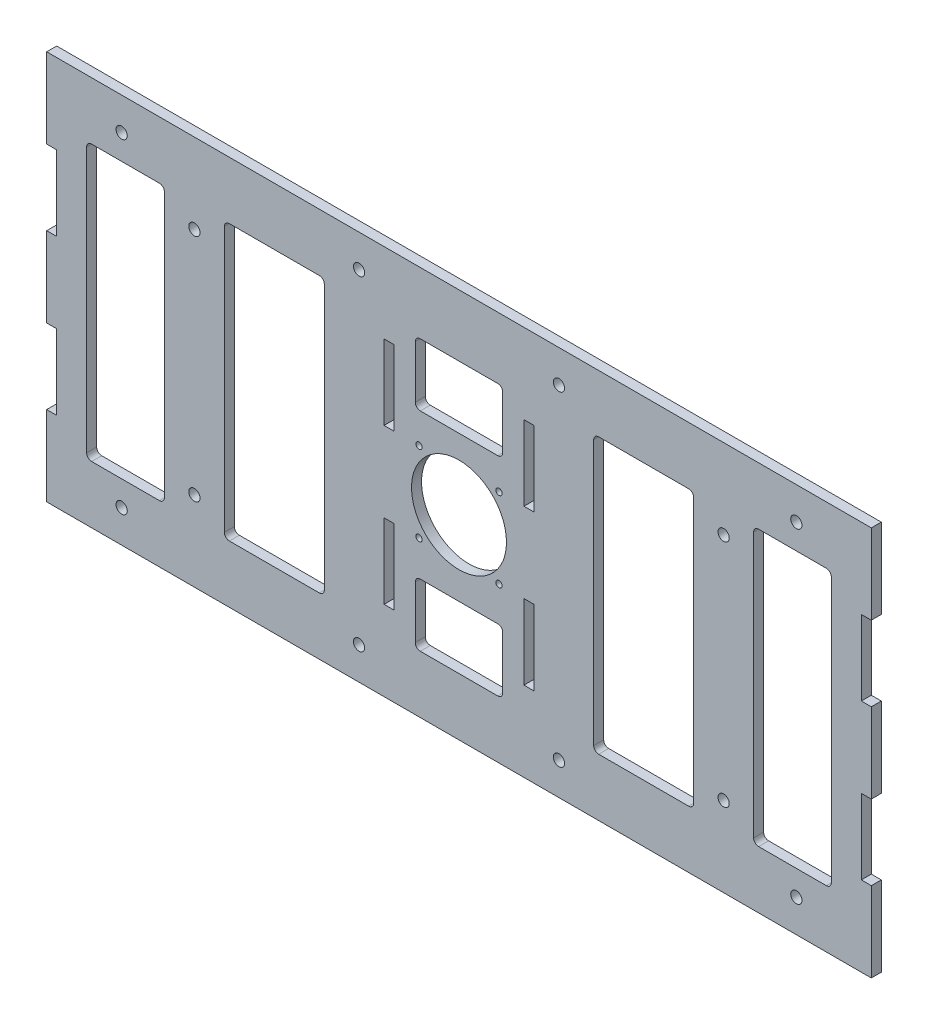
SolidWorks part; units mm, degrees
ref_plane "Ebene vorne" through (0, 0, 0) normal (0, 0, 1) x (1, 0, 0)
ref_plane "Ebene oben" through (0, 0, 0) normal (0, 1, 0) x (1, 0, 0)
ref_plane "Ebene rechts" through (0, 0, 0) normal (1, 0, 0) x (0, 0, -1)
sketch "Skizze1" plane through (0, 0, 0) normal (0, 0, 1) x (1, 0, 0)
  line L1 (165, -78) -> (-165, -78)
  line L2 (165, -78) -> (165, 78)
  line L3 (165, 78) -> (-165, 78)
  line L4 (-165, -78) -> (-165, 78)
  line L5 (165, -78) -> (-165, 78) construction
  line L6 (165, 78) -> (-165, -78) construction
  point P0 (0, 0)
  dimension "D1" = 156
  dimension "D2" = 330
extrude "Aufsatz-Linear austragen1" add sketch "Skizze1" along normal blind 4
sketch "Skizze2" plane through (0, 0, 4) normal (0, 0, 1) x (1, 0, 0)
  line L0 (-165, 65) -> (165, 65) construction
  line L1 (-165, 78) -> (-165, -78) construction
  line L2 (165, -78) -> (165, 78) construction
  line L3 (0, 78) -> (0, -78) construction
  line L4 (165, 78) -> (-165, 78) construction
  line L5 (-165, -78) -> (165, -78) construction
  line L6 (-165, -65) -> (165, -65) construction
  line L7 (-105.9, 65) -> (-105.9, -65) construction
  line L8 (105.9, 65) -> (105.9, -65) construction
  line L9 (-165, 46) -> (165, 46) construction
  line L10 (-165, -46) -> (165, -46) construction
  line L11 (149, -55) -> (117.9, -55)
  line L12 (-149, 55) -> (-117.9, 55)
  line L13 (-149, 55) -> (-149, -55)
  line L14 (-149, -55) -> (-117.9, -55)
  line L15 (-117.9, 55) -> (-117.9, -55)
  line L16 (117.9, 55) -> (117.9, -55)
  line L17 (149, 55) -> (117.9, 55)
  line L18 (149, 55) -> (149, -55)
  line L19 (-40, 65) -> (-40, -65) construction
  line L20 (40, 65) -> (40, -65) construction
  line L21 (-165, 0) -> (165, 0) construction
  line L28 (-25.9951, 0) -> (-40, -11.9903) construction
  line L34 (-135, 65) -> (-135, -65) construction
  circle A2 centre (-105.9, 46) radius 2.25
  circle A3 centre (-105.9, -46) radius 2.25
  circle A4 centre (105.9, -46) radius 2.25
  circle A5 centre (105.9, 46) radius 2.25
  circle A6 centre (-40, 65) radius 2.25
  circle A7 centre (40, 65) radius 2.25
  circle A8 centre (-40, -65) radius 2.25
  circle A9 centre (40, -65) radius 2.25
  circle A10 centre (-135, -65) radius 2.25
  circle A11 centre (-135, 65) radius 2.25
  circle A12 centre (135, -65) radius 2.25
  circle A13 centre (135, 65) radius 2.25
  point P48 (-25.9951, 0)
  point P57 (25.9951, 0)
  dimension "D3" = 4.5
  dimension "D1" = 13
  dimension "D2" = 13
  dimension "D4" = 59.1
  dimension "D5" = 59.1
  dimension "D6" = 32
  dimension "D7" = 32
  dimension "D8" = 23
  dimension "D9" = 23
  dimension "D10" = 12
  dimension "D12" = 40
  dimension "D13" = 40
  dimension "D11" = 16
extrude "Schnitt-Linear austragen1" cut sketch "Skizze2" against normal through all
sketch "Skizze3" plane through (0, 0, 4) normal (0, 0, 1) x (1, 0, 0)
  line L0 (0, 78) -> (0, -78) construction
  line L1 (165, 78) -> (-165, 78) construction
  line L2 (-165, -78) -> (165, -78) construction
  line L4 (-20, -20) -> (20, -20) construction
  line L5 (-20, -20) -> (-20, 20) construction
  line L6 (-20, 20) -> (20, 20) construction
  line L7 (20, -20) -> (20, 20) construction
  line L8 (-20, -20) -> (20, 20) construction
  line L9 (-20, 20) -> (20, -20) construction
  line L10 (-16, -16) -> (16, -16) construction
  line L11 (-16, -16) -> (-16, 16) construction
  line L12 (-16, 16) -> (16, 16) construction
  line L13 (16, -16) -> (16, 16) construction
  line L14 (-16, -16) -> (16, 16) construction
  line L15 (-16, 16) -> (16, -16) construction
  point P6 (0, 0)
  point P11 (0, 0)
  point P12 (16, 16)
  point P14 (-16, -16)
  point P15 (-16, 16)
  point P16 (16, -16)
  dimension "D1" = 40
  dimension "D3" = 32
hole_wizard "M3 Gewindebohrung1" positions "Skizze3" profile "Skizze4" tap size "M3" standard "DIN" end condition through all
sketch "Skizze4" plane through (16, -16, 4) normal (1, 0, 0) x (0, -1, 0)
  line L0 (0, 0) -> (0, 4)
  line L1 (0, 4) -> (1.25, 4)
  line L2 (1.25, 4) -> (1.25, 0)
  line L5 (1.25, 0) -> (0, 0)
  line L11 (0, -6.35) -> (0, 107.95) construction
  dimension "Bohrerdurchmesser" = 2.5
  dimension "Bohrungstiefe" = 4
sketch "Skizze5" plane through (0, 0, 4) normal (0, 0, 1) x (1, 0, 0)
  circle A0 centre (0, 0) radius 19
  dimension "D1" = 38
extrude "Schnitt-Linear austragen2" cut sketch "Skizze5" against normal through all contours A0
sketch "Skizze7" plane through (0, 0, 4) normal (0, 0, 1) x (1, 0, 0)
  line L0 (-30.2968, -0.8563) -> (29.426, -0.8563) construction
  line L1 (-165, -78) -> (165, -78) construction
  line L8 (0, 73.9526) -> (0, -71.9477) construction
  line L13 (-17.5, -55) -> (17.5, -55)
  line L14 (-17.5, -55) -> (-17.5, -30)
  line L15 (-17.5, -30) -> (17.5, -30)
  line L16 (17.5, -55) -> (17.5, -30)
  line L17 (-17.5, -55) -> (17.5, -30) construction
  line L23 (-17.5, -30) -> (17.5, -55) construction
  line L24 (-17.5, 28.2873) -> (17.5, 53.2873) construction
  line L25 (-17.5, 53.2873) -> (17.5, 28.2873) construction
  line L26 (17.5, 53.2873) -> (17.5, 28.2873)
  line L27 (-17.5, 28.2873) -> (17.5, 28.2873)
  line L28 (-17.5, 53.2873) -> (-17.5, 28.2873)
  line L29 (-17.5, 53.2873) -> (17.5, 53.2873)
  point P6 (0, 40.7873)
  point P9 (0, -42.5)
  dimension "D1" = 25
  dimension "D6" = 35
  dimension "D7" = 23
extrude "Schnitt-Linear austragen3" cut sketch "Skizze7" against normal through all
fillet "Verrundung1" radius 2 16 edges at (149, 55, 2) (117.9, 55, 2) (149, -55, 2) (117.9, -55, 2) (-149, -55, 2) (-117.9, -55, 2) (-117.9, 55, 2) (-149, 55, 2) (-17.5, -55, 2) (17.5, -30, 2) (17.5, -55, 2) (-17.5, -30, 2) (17.5, 53.2873, 2) (17.5, 28.2873, 2) (-17.5, 28.2873, 2) (-17.5, 53.2873, 2)
sketch "Skizze8" plane through (0, 0, 4) normal (0, 0, 1) x (1, 0, 0)
  line L0 (-149, 0) -> (149, 0) construction
  line L1 (-149, 53) -> (-149, -53) construction
  line L2 (149, -53) -> (149, 53) construction
  line L3 (-93.9, 9) -> (-93.9, -9)
  line L4 (-91.9, -55) -> (-55.9, -55)
  line L5 (-93.9, -53) -> (-93.9, -9)
  line L6 (-91.9, 55) -> (-55.9, 55)
  line L7 (-53.9, -53) -> (-53.9, -9)
  line L8 (-93.9, -55) -> (-53.9, 55) construction
  line L9 (-93.9, 55) -> (-53.9, -55) construction
  line L10 (-53.9, 9) -> (-53.9, -9)
  line L11 (-117.9, -53) -> (-117.9, 53) construction
  line L14 (-93.9, 9) -> (-93.9, 53)
  line L15 (-53.9, 9) -> (-53.9, 53)
  line L16 (0, -2.2) -> (0, 2.2) construction
  line L17 (93.9, 55) -> (53.9, -55) construction
  line L18 (93.9, -55) -> (53.9, 55) construction
  line L19 (53.9, 9) -> (53.9, 53)
  line L20 (93.9, 9) -> (93.9, 53)
  line L23 (53.9, -53) -> (53.9, -9)
  line L24 (91.9, 55) -> (55.9, 55)
  line L25 (93.9, -53) -> (93.9, -9)
  line L26 (91.9, -55) -> (55.9, -55)
  line L27 (53.9, 9) -> (53.9, -9)
  line L28 (93.9, 9) -> (93.9, -9)
  arc A0 (-91.9, -55) -> (-93.9, -53) centre (-91.9, -53) cw
  arc A1 (-55.9, -55) -> (-53.9, -53) centre (-55.9, -53) ccw
  arc A6 (-55.9, 55) -> (-53.9, 53) centre (-55.9, 53) cw
  arc A7 (-93.9, 53) -> (-91.9, 55) centre (-91.9, 53) cw
  arc A8 (93.9, 53) -> (91.9, 55) centre (91.9, 53) ccw
  arc A9 (55.9, 55) -> (53.9, 53) centre (55.9, 53) ccw
  arc A14 (55.9, -55) -> (53.9, -53) centre (55.9, -53) cw
  arc A15 (91.9, -55) -> (93.9, -53) centre (91.9, -53) ccw
  point P6 (-73.9, 0)
  point P29 (-93.9, 7)
  point P32 (-53.9, 7)
  point P69 (53.9, 7)
  point P70 (93.9, 7)
  point P71 (73.9, 0)
  dimension "D6" = 2
  dimension "D1" = 110
  dimension "D2" = 40
  dimension "D3" = 24
extrude "Schnitt-Linear austragen4" cut sketch "Skizze8" against normal through all
sketch "Skizze9" plane through (0, 0, 4) normal (0, 0, 1) x (1, 0, 0)
  line L0 (-165, 78) -> (-165, -78) construction
  line L1 (-165, 46) -> (-161, 46)
  line L2 (-165, 46) -> (-165, 16)
  line L3 (-165, 16) -> (-161, 16)
  line L4 (-161, 46) -> (-161, 16)
  line L5 (165, 78) -> (-165, 78) construction
  line L6 (2.2, 0) -> (-2.2, 0) construction
  line L7 (-161, -46) -> (-161, -16)
  line L8 (-165, -16) -> (-161, -16)
  line L9 (-165, -46) -> (-165, -16)
  line L10 (-165, -46) -> (-161, -46)
  line L11 (0, -2.2) -> (0, 2.2) construction
  line L12 (165, -46) -> (161, -46)
  line L13 (165, -46) -> (165, -16)
  line L14 (165, -16) -> (161, -16)
  line L15 (161, -46) -> (161, -16)
  line L16 (161, 46) -> (161, 16)
  line L17 (165, 16) -> (161, 16)
  line L18 (165, 46) -> (165, 16)
  line L19 (165, 46) -> (161, 46)
  line L20 (-26, -46) -> (-26, -16)
  line L21 (-30, 46) -> (-26, 46)
  line L22 (-30, 46) -> (-30, 16)
  line L23 (-30, 16) -> (-26, 16)
  line L24 (-26, 46) -> (-26, 16)
  line L25 (-30, -16) -> (-26, -16)
  line L26 (-30, -46) -> (-30, -16)
  line L27 (-30, -46) -> (-26, -46)
  line L28 (30, -46) -> (26, -46)
  line L29 (30, -46) -> (30, -16)
  line L30 (30, -16) -> (26, -16)
  line L31 (26, 46) -> (26, 16)
  line L32 (30, 16) -> (26, 16)
  line L33 (30, 46) -> (30, 16)
  line L34 (30, 46) -> (26, 46)
  line L35 (26, -46) -> (26, -16)
  dimension "D1" = 30
  dimension "D2" = 4
  dimension "D3" = 32
  dimension "D4" = 30
  dimension "D5" = 4
  dimension "D6" = 32
  dimension "D7" = 135
extrude "Schnitt-Linear austragen5" cut sketch "Skizze9" against normal through all
equation "\"D13@Skizze2\"=\"D12@Skizze2\""
equation "\"D5@Skizze2\"=\"D4@Skizze2\""
equation "\"D2@Skizze2\"=\"D1@Skizze2\""
equation "\"D8@Skizze2\"=\"D9@Skizze2\""
